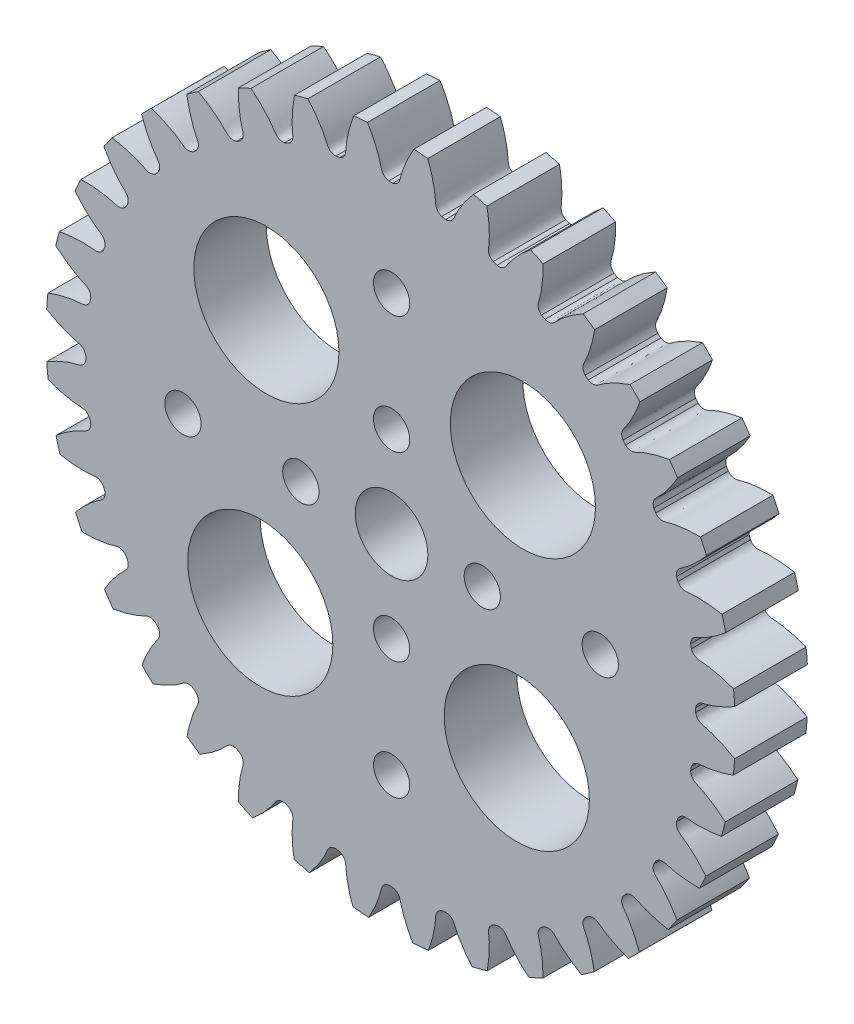
SolidWorks part; units mm, degrees
ref_plane "前视基准面" through (0, 0, 0) normal (0, 0, 1) x (1, 0, 0)
ref_plane "上视基准面" through (0, 0, 0) normal (0, 1, 0) x (1, 0, 0)
ref_plane "右视基准面" through (0, 0, 0) normal (1, 0, 0) x (0, 0, -1)
sketch "草图1" plane through (0, 0, 0) normal (0, 0, 1) x (1, 0, 0)
  circle A0 centre (-456.4903, -117.4676) radius 2
  circle A1 centre (-451.4903, -117.4676) radius 1
  circle A2 centre (-456.4903, -112.4676) radius 1
  circle A3 centre (-461.4903, -117.4676) radius 1
  circle A4 centre (-456.4903, -122.4676) radius 1
  arc A5 (-459.348, -100.9266) -> (-459.5644, -100.9647) centre (-456.5477, -117.4408) ccw
  arc A6 (-456.4282, -100.6904) -> (-456.648, -100.6904) centre (-456.5381, -117.44) ccw
  arc A7 (-454.4982, -98.5498) -> (-455.2571, -98.4832) centre (-456.5381, -117.44) ccw
  arc A8 (-453.5118, -100.9647) -> (-453.7282, -100.9266) centre (-456.5285, -117.4408) ccw
  arc A9 (-450.6873, -101.7414) -> (-450.8938, -101.6662) centre (-456.5192, -117.4433) ccw
  arc A10 (-448.0406, -102.9967) -> (-448.2309, -102.8868) centre (-456.5105, -117.4474) ccw
  arc A11 (-445.652, -104.6926) -> (-445.8204, -104.5513) centre (-456.5027, -117.4529) ccw
  arc A12 (-443.5943, -106.7774) -> (-443.7355, -106.6091) centre (-456.4959, -117.4597) ccw
  arc A13 (-441.9298, -109.1879) -> (-442.0397, -108.9976) centre (-456.4903, -117.4676) ccw
  arc A14 (-440.7092, -111.8508) -> (-440.7843, -111.6443) centre (-456.4863, -117.4763) ccw
  arc A15 (-439.9695, -114.6852) -> (-440.0077, -114.4688) centre (-456.4838, -117.4856) ccw
  arc A16 (-439.7333, -117.605) -> (-439.7333, -117.3853) centre (-456.483, -117.4951) ccw
  arc A17 (-440.0077, -120.5215) -> (-439.9695, -120.3051) centre (-456.4838, -117.5047) ccw
  arc A18 (-440.7843, -123.346) -> (-440.7092, -123.1395) centre (-456.4863, -117.514) ccw
  arc A19 (-442.0397, -125.9927) -> (-441.9298, -125.8024) centre (-456.4903, -117.5227) ccw
  arc A20 (-443.7355, -128.3812) -> (-443.5943, -128.2129) centre (-456.4959, -117.5306) ccw
  arc A21 (-445.8204, -130.439) -> (-445.652, -130.2977) centre (-456.5027, -117.5374) ccw
  arc A22 (-448.2309, -132.1035) -> (-448.0406, -131.9936) centre (-456.5105, -117.5429) ccw
  arc A23 (-450.8938, -133.3241) -> (-450.6873, -133.2489) centre (-456.5192, -117.547) ccw
  arc A24 (-453.7282, -134.0637) -> (-453.5118, -134.0256) centre (-456.5285, -117.5495) ccw
  arc A25 (-456.648, -134.2999) -> (-456.4282, -134.2999) centre (-456.5381, -117.5503) ccw
  arc A26 (-459.5644, -134.0256) -> (-459.348, -134.0637) centre (-456.5477, -117.5495) ccw
  arc A27 (-462.3889, -133.2489) -> (-462.1824, -133.3241) centre (-456.557, -117.547) ccw
  arc A28 (-465.0356, -131.9936) -> (-464.8454, -132.1035) centre (-456.5657, -117.5429) ccw
  arc A29 (-467.4242, -130.2977) -> (-467.2559, -130.439) centre (-456.5736, -117.5374) ccw
  arc A30 (-469.4819, -128.2129) -> (-469.3407, -128.3812) centre (-456.5804, -117.5306) ccw
  arc A31 (-471.1464, -125.8024) -> (-471.0365, -125.9927) centre (-456.5859, -117.5227) ccw
  arc A32 (-472.367, -123.1395) -> (-472.2919, -123.346) centre (-456.5899, -117.514) ccw
  arc A33 (-473.1067, -120.3051) -> (-473.0685, -120.5215) centre (-456.5924, -117.5047) ccw
  arc A34 (-473.3429, -117.3853) -> (-473.3429, -117.605) centre (-456.5933, -117.4951) ccw
  arc A35 (-473.0685, -114.4688) -> (-473.1067, -114.6852) centre (-456.5924, -117.4856) ccw
  arc A36 (-472.2919, -111.6443) -> (-472.367, -111.8508) centre (-456.5899, -117.4763) ccw
  arc A37 (-471.0365, -108.9976) -> (-471.1464, -109.1879) centre (-456.5859, -117.4676) ccw
  arc A38 (-469.3407, -106.6091) -> (-469.4819, -106.7774) centre (-456.5804, -117.4597) ccw
  arc A39 (-467.2559, -104.5513) -> (-467.4242, -104.6926) centre (-456.5736, -117.4529) ccw
  arc A40 (-464.8454, -102.8868) -> (-465.0357, -102.9967) centre (-456.5657, -117.4474) ccw
  arc A41 (-462.1824, -101.6662) -> (-462.3889, -101.7414) centre (-456.557, -117.4433) ccw
  arc A42 (-451.2389, -99.1939) -> (-451.9763, -98.9958) centre (-456.5381, -117.44) ccw
  arc A43 (-448.1414, -100.3961) -> (-448.8359, -100.0712) centre (-456.5381, -117.44) ccw
  arc A44 (-445.3006, -102.1194) -> (-445.9319, -101.6759) centre (-456.5381, -117.44) ccw
  arc A45 (-442.8037, -104.3111) -> (-443.3524, -103.7602) centre (-456.5381, -117.44) ccw
  arc A46 (-440.7271, -106.9037) -> (-441.1757, -106.2598) centre (-456.5381, -117.44) ccw
  arc A47 (-439.1341, -109.8175) -> (-439.4673, -109.098) centre (-456.5381, -117.44) ccw
  arc A48 (-438.0731, -112.963) -> (-438.2784, -112.1881) centre (-456.5381, -117.44) ccw
  arc A49 (-437.5758, -116.2437) -> (-437.6441, -115.4357) centre (-456.5381, -117.44) ccw
  arc A50 (-437.6567, -119.5593) -> (-437.5828, -118.7425) centre (-456.5381, -117.44) ccw
  arc A51 (-438.3123, -122.8086) -> (-438.0954, -122.0082) centre (-456.5381, -117.44) ccw
  arc A52 (-439.5219, -125.8928) -> (-439.1658, -125.1343) centre (-456.5381, -117.44) ccw
  arc A53 (-441.2477, -128.7185) -> (-440.7609, -128.0267) centre (-456.5381, -117.44) ccw
  arc A54 (-443.4365, -131.2004) -> (-442.8322, -130.5986) centre (-456.5381, -117.44) ccw
  arc A55 (-446.0213, -133.2639) -> (-445.317, -132.7725) centre (-456.5381, -117.44) ccw
  arc A56 (-448.9232, -134.8473) -> (-448.1403, -134.4834) centre (-456.5381, -117.44) ccw
  arc A57 (-452.0543, -135.9034) -> (-451.2172, -135.6797) centre (-456.5381, -117.44) ccw
  arc A58 (-455.3198, -136.4009) -> (-454.455, -136.3255) centre (-456.5381, -117.44) ccw
  arc A59 (-458.6212, -136.3255) -> (-457.7564, -136.4009) centre (-456.5381, -117.44) ccw
  arc A60 (-461.859, -135.6797) -> (-461.0219, -135.9034) centre (-456.5381, -117.44) ccw
  arc A61 (-464.9359, -134.4834) -> (-464.153, -134.8473) centre (-456.5381, -117.44) ccw
  arc A62 (-467.7592, -132.7725) -> (-467.0549, -133.2639) centre (-456.5381, -117.44) ccw
  arc A63 (-470.244, -130.5986) -> (-469.6397, -131.2004) centre (-456.5381, -117.44) ccw
  arc A64 (-472.3153, -128.0267) -> (-471.8285, -128.7185) centre (-456.5381, -117.44) ccw
  arc A65 (-473.9104, -125.1343) -> (-473.5543, -125.8928) centre (-456.5381, -117.44) ccw
  arc A66 (-474.9808, -122.0082) -> (-474.7639, -122.8086) centre (-456.5381, -117.44) ccw
  arc A67 (-475.4934, -118.7425) -> (-475.4195, -119.5593) centre (-456.5381, -117.44) ccw
  arc A68 (-475.4321, -115.4357) -> (-475.5004, -116.2437) centre (-456.5381, -117.44) ccw
  arc A69 (-474.7978, -112.1881) -> (-475.0031, -112.963) centre (-456.5381, -117.44) ccw
  arc A70 (-473.6089, -109.098) -> (-473.9421, -109.8175) centre (-456.5381, -117.44) ccw
  arc A71 (-471.9005, -106.2598) -> (-472.3491, -106.9037) centre (-456.5381, -117.44) ccw
  arc A72 (-469.7238, -103.7602) -> (-470.2725, -104.3111) centre (-456.5381, -117.44) ccw
  arc A73 (-467.1444, -101.6759) -> (-467.7756, -102.1194) centre (-456.5381, -117.44) ccw
  arc A74 (-464.2403, -100.0712) -> (-464.9348, -100.3961) centre (-456.5381, -117.44) ccw
  arc A75 (-461.0999, -98.9958) -> (-461.8373, -99.1939) centre (-456.5381, -117.44) ccw
  arc A76 (-457.8191, -98.4832) -> (-458.578, -98.5498) centre (-456.5381, -117.44) ccw
  circle A77 centre (-463.3906, -110.2298) radius 4
  circle A78 centre (-463.7281, -124.3679) radius 4
  circle A79 centre (-449.59, -124.7054) radius 4
  circle A80 centre (-449.2525, -110.5673) radius 4
  circle A81 centre (-456.4903, -128.9676) radius 1
  circle A82 centre (-444.9903, -117.4676) radius 1
  circle A83 centre (-456.4903, -105.9676) radius 1
  circle A84 centre (-467.9903, -117.4676) radius 1
  spline S0 degree 3 poles (-459.348, -100.9266) (-459.0074, -100.7845) (-459.0234, -100.515) (-458.9985, -100.2221) (-458.9898, -100.1383) (-458.9743, -100.0135) (-458.9476, -99.8415) (-458.9033, -99.6165) (-458.8439, -99.3672) (-458.7672, -99.0943) (-458.6778, -98.8188) (-458.6108, -98.6354) (-458.578, -98.5498) knots 0 0 0 0 0.120371 0.133303 0.147364 0.162556 0.19633 0.234626 0.277443 0.324782 0.376641 0.422597 0.422597 0.422597 0.422597
  spline S1 degree 3 poles (-456.648, -100.6904) (-457.0081, -100.6096) (-457.0391, -100.3414) (-457.1145, -100.0572) (-457.1376, -99.9763) (-457.1745, -99.8561) (-457.2308, -99.6913) (-457.3134, -99.4774) (-457.4153, -99.2422) (-457.5381, -98.9868) (-457.6741, -98.7309) (-457.7719, -98.5619) (-457.8191, -98.4832) knots 0 0 0 0 0.120371 0.133303 0.147364 0.162556 0.19633 0.234626 0.277443 0.324782 0.376641 0.422634 0.422634 0.422634 0.422634
  spline S2 degree 3 poles (-456.4282, -100.6904) (-456.0681, -100.6096) (-456.0371, -100.3414) (-455.9617, -100.0572) (-455.9386, -99.9763) (-455.9017, -99.8561) (-455.8454, -99.6913) (-455.7628, -99.4774) (-455.661, -99.2422) (-455.5381, -98.9868) (-455.4021, -98.7309) (-455.3043, -98.5619) (-455.2571, -98.4832) knots 0 0 0 0 0.120371 0.133303 0.147364 0.162556 0.19633 0.234626 0.277443 0.324782 0.376641 0.422634 0.422634 0.422634 0.422634
  spline S3 degree 3 poles (-453.7282, -100.9266) (-454.0688, -100.7845) (-454.0528, -100.515) (-454.0777, -100.2221) (-454.0864, -100.1383) (-454.1019, -100.0135) (-454.1286, -99.8415) (-454.1729, -99.6165) (-454.2323, -99.3672) (-454.309, -99.0943) (-454.3984, -98.8188) (-454.4654, -98.6354) (-454.4982, -98.5498) knots 0 0 0 0 0.120371 0.133303 0.147364 0.162556 0.19633 0.234626 0.277443 0.324782 0.376641 0.422597 0.422597 0.422597 0.422597
  spline S4 degree 3 poles (-453.5118, -100.9647) (-453.1431, -100.9477) (-453.066, -100.689) (-452.9424, -100.4223) (-452.9056, -100.3465) (-452.8484, -100.2346) (-452.7644, -100.082) (-452.6458, -99.8858) (-452.5047, -99.6718) (-452.3393, -99.4416) (-452.1613, -99.2137) (-452.0361, -99.0646) (-451.9763, -98.9958) knots 0 0 0 0 0.120371 0.133303 0.147364 0.162556 0.19633 0.234626 0.277443 0.324782 0.376641 0.422355 0.422355 0.422355 0.422355
  spline S5 degree 3 poles (-450.8938, -101.6662) (-451.2045, -101.4672) (-451.1419, -101.2045) (-451.1157, -100.9117) (-451.1096, -100.8278) (-451.1032, -100.7022) (-451.0997, -100.5281) (-451.1042, -100.2988) (-451.1195, -100.043) (-451.1476, -99.7609) (-451.1877, -99.4748) (-451.2217, -99.2833) (-451.2389, -99.1939) knots 0 0 0 0 0.120371 0.133303 0.147364 0.162556 0.19633 0.234626 0.277443 0.324782 0.376641 0.422247 0.422247 0.422247 0.422247
  spline S6 degree 3 poles (-450.6873, -101.7414) (-450.3213, -101.7887) (-450.2004, -101.5472) (-450.0323, -101.306) (-449.983, -101.2378) (-449.9071, -101.1375) (-449.7979, -101.0019) (-449.6471, -100.8292) (-449.471, -100.643) (-449.2682, -100.445) (-449.0542, -100.2522) (-448.9058, -100.1279) (-448.8359, -100.0712) knots 0 0 0 0 0.120371 0.133303 0.147364 0.162556 0.19633 0.234626 0.277443 0.324782 0.376641 0.421771 0.421771 0.421771 0.421771
  spline S7 degree 3 poles (-448.2309, -102.8868) (-448.5023, -102.6368) (-448.3951, -102.389) (-448.3184, -102.1053) (-448.2979, -102.0236) (-448.2697, -101.9011) (-448.236, -101.7302) (-448.2007, -101.5037) (-448.1712, -101.249) (-448.15, -100.9664) (-448.1399, -100.6789) (-448.14, -100.4857) (-448.1414, -100.3961) knots 0 0 0 0 0.120371 0.133303 0.147364 0.162556 0.19633 0.234626 0.277443 0.324782 0.376641 0.421594 0.421594 0.421594 0.421594
  spline S8 degree 3 poles (-448.0406, -102.9967) (-447.6883, -103.1068) (-447.5273, -102.89) (-447.3199, -102.6817) (-447.2595, -102.6231) (-447.1674, -102.5375) (-447.0363, -102.4229) (-446.8578, -102.279) (-446.652, -102.1262) (-446.4179, -101.9665) (-446.1751, -101.8147) (-446.009, -101.7188) (-445.9319, -101.6759) knots 0 0 0 0 0.120371 0.133303 0.147364 0.162556 0.19633 0.234626 0.277443 0.324782 0.376641 0.420899 0.420899 0.420899 0.420899
  spline S9 degree 3 poles (-445.8204, -104.5513) (-446.0443, -104.258) (-445.8957, -104.0326) (-445.7708, -103.7664) (-445.7364, -103.6896) (-445.6875, -103.5737) (-445.6246, -103.4113) (-445.5504, -103.1944) (-445.4773, -102.9487) (-445.4072, -102.6741) (-445.3477, -102.3946) (-445.3145, -102.2062) (-445.3006, -102.1194) knots 0 0 0 0 0.120371 0.133303 0.147364 0.162556 0.19633 0.234626 0.277443 0.324782 0.376641 0.420658 0.420658 0.420658 0.420658
  spline S10 degree 3 poles (-445.652, -104.6926) (-445.3243, -104.8621) (-445.1281, -104.6766) (-444.8877, -104.5075) (-444.818, -104.4603) (-444.7124, -104.3919) (-444.5634, -104.3018) (-444.3626, -104.1911) (-444.1334, -104.0764) (-443.8751, -103.9597) (-443.6118, -103.8533) (-443.4337, -103.7884) (-443.3524, -103.7602) knots 0 0 0 0 0.120371 0.133303 0.147364 0.162556 0.19633 0.234626 0.277443 0.324782 0.376641 0.419767 0.419767 0.419767 0.419767
  spline S11 degree 3 poles (-443.7355, -106.6091) (-443.9051, -106.2813) (-443.7196, -106.0851) (-443.5504, -105.8447) (-443.5032, -105.775) (-443.4349, -105.6694) (-443.3448, -105.5204) (-443.2341, -105.3197) (-443.1193, -105.0904) (-443.0027, -104.8321) (-442.8964, -104.5694) (-442.8318, -104.3918) (-442.8037, -104.3111) knots 0 0 0 0 0.120371 0.133303 0.147364 0.162556 0.19633 0.234626 0.277443 0.324782 0.376641 0.419468 0.419468 0.419468 0.419468
  spline S12 degree 3 poles (-443.5943, -106.7774) (-443.3009, -107.0013) (-443.0755, -106.8527) (-442.8094, -106.7279) (-442.7325, -106.6935) (-442.6167, -106.6445) (-442.4543, -106.5816) (-442.2374, -106.5075) (-441.9917, -106.4343) (-441.7171, -106.3643) (-441.4419, -106.3057) (-441.258, -106.2732) (-441.1757, -106.2598) knots 0 0 0 0 0.120371 0.133303 0.147364 0.162556 0.19633 0.234626 0.277443 0.324782 0.376641 0.418409 0.418409 0.418409 0.418409
  spline S13 degree 3 poles (-442.0397, -108.9976) (-442.1498, -108.6454) (-441.933, -108.4844) (-441.7247, -108.277) (-441.6661, -108.2165) (-441.5804, -108.1245) (-441.4658, -107.9933) (-441.3219, -107.8148) (-441.1691, -107.609) (-441.0094, -107.3749) (-440.8606, -107.137) (-440.7675, -106.9759) (-440.7271, -106.9037) knots 0 0 0 0 0.120371 0.133303 0.147364 0.162556 0.19633 0.234626 0.277443 0.324782 0.376641 0.418059 0.418059 0.418059 0.418059
  spline S14 degree 3 poles (-441.9298, -109.1879) (-441.6798, -109.4594) (-441.432, -109.3521) (-441.1482, -109.2754) (-441.0666, -109.2549) (-440.944, -109.2268) (-440.7732, -109.1931) (-440.5466, -109.1577) (-440.292, -109.1283) (-440.0094, -109.107) (-439.7313, -109.0972) (-439.5476, -109.097) (-439.4673, -109.098) knots 0 0 0 0 0.120371 0.133303 0.147364 0.162556 0.19633 0.234626 0.277443 0.324782 0.376641 0.416867 0.416867 0.416867 0.416867
  spline S15 degree 3 poles (-440.7843, -111.6443) (-440.8316, -111.2783) (-440.5902, -111.1574) (-440.349, -110.9894) (-440.2808, -110.94) (-440.1805, -110.8642) (-440.0448, -110.755) (-439.8721, -110.6042) (-439.6859, -110.428) (-439.488, -110.2252) (-439.3023, -110.0191) (-439.1845, -109.879) (-439.1341, -109.8175) knots 0 0 0 0 0.120371 0.133303 0.147364 0.162556 0.19633 0.234626 0.277443 0.324782 0.376641 0.416476 0.416476 0.416476 0.416476
  spline S16 degree 3 poles (-440.7092, -111.8508) (-440.5101, -112.1616) (-440.2475, -112.099) (-439.9547, -112.0727) (-439.8707, -112.0667) (-439.7451, -112.0603) (-439.571, -112.0567) (-439.3418, -112.0613) (-439.0859, -112.0765) (-438.8039, -112.1046) (-438.5317, -112.1428) (-438.354, -112.1738) (-438.2784, -112.1881) knots 0 0 0 0 0.120371 0.133303 0.147364 0.162556 0.19633 0.234626 0.277443 0.324782 0.376641 0.415189 0.415189 0.415189 0.415189
  spline S17 degree 3 poles (-440.0077, -114.4688) (-439.9907, -114.1002) (-439.7319, -114.023) (-439.4652, -113.8994) (-439.3895, -113.8626) (-439.2775, -113.8054) (-439.125, -113.7214) (-438.9287, -113.6029) (-438.7147, -113.4617) (-438.4846, -113.2964) (-438.2686, -113.1277) (-438.1308, -113.0126) (-438.0731, -112.963) knots 0 0 0 0 0.120371 0.133303 0.147364 0.162556 0.19633 0.234626 0.277443 0.324782 0.376641 0.414768 0.414768 0.414768 0.414768
  spline S18 degree 3 poles (-439.9695, -114.6852) (-439.8275, -115.0258) (-439.5579, -115.0098) (-439.265, -115.0348) (-439.1813, -115.0434) (-439.0565, -115.0589) (-438.8844, -115.0857) (-438.6595, -115.1299) (-438.4101, -115.1894) (-438.1373, -115.266) (-437.8792, -115.3498) (-437.7128, -115.4099) (-437.6441, -115.4357) knots 0 0 0 0 0.120371 0.133303 0.147364 0.162556 0.19633 0.234626 0.277443 0.324782 0.376641 0.413425 0.413425 0.413425 0.413425
  spline S19 degree 3 poles (-439.7333, -117.3853) (-439.6526, -117.0252) (-439.3843, -116.9942) (-439.1002, -116.9187) (-439.0193, -116.8956) (-438.899, -116.8587) (-438.7342, -116.8025) (-438.5204, -116.7198) (-438.2851, -116.618) (-438.0298, -116.4951) (-437.7909, -116.3682) (-437.6382, -116.2806) (-437.5758, -116.2437) knots 0 0 0 0 0.120371 0.133303 0.147364 0.162556 0.19633 0.234626 0.277443 0.324782 0.376641 0.412986 0.412986 0.412986 0.412986
  spline S20 degree 3 poles (-439.7333, -117.605) (-439.6526, -117.9651) (-439.3843, -117.9961) (-439.1002, -118.0716) (-439.0193, -118.0946) (-438.899, -118.1316) (-438.7342, -118.1878) (-438.5204, -118.2704) (-438.2851, -118.3723) (-438.0298, -118.4952) (-437.7933, -118.6208) (-437.6429, -118.707) (-437.5828, -118.7425) knots 0 0 0 0 0.120371 0.133303 0.147364 0.162556 0.19633 0.234626 0.277443 0.324782 0.376641 0.411628 0.411628 0.411628 0.411628
  spline S21 degree 3 poles (-439.9695, -120.3051) (-439.8275, -119.9645) (-439.5579, -119.9805) (-439.265, -119.9555) (-439.1813, -119.9469) (-439.0565, -119.9314) (-438.8844, -119.9046) (-438.6595, -119.8604) (-438.4101, -119.8009) (-438.1373, -119.7242) (-437.8834, -119.6418) (-437.7212, -119.5834) (-437.6567, -119.5593) knots 0 0 0 0 0.120371 0.133303 0.147364 0.162556 0.19633 0.234626 0.277443 0.324782 0.376641 0.411185 0.411185 0.411185 0.411185
  spline S22 degree 3 poles (-440.0077, -120.5215) (-439.9907, -120.8901) (-439.7319, -120.9673) (-439.4652, -121.0909) (-439.3895, -121.1277) (-439.2775, -121.1849) (-439.125, -121.2689) (-438.9287, -121.3874) (-438.7147, -121.5286) (-438.4846, -121.6939) (-438.2763, -121.8566) (-438.1459, -121.9652) (-438.0954, -122.0082) knots 0 0 0 0 0.120371 0.133303 0.147364 0.162556 0.19633 0.234626 0.277443 0.324782 0.376641 0.409854 0.409854 0.409854 0.409854
  spline S23 degree 3 poles (-440.7092, -123.1395) (-440.5101, -122.8287) (-440.2475, -122.8913) (-439.9547, -122.9176) (-439.8707, -122.9236) (-439.7451, -122.93) (-439.571, -122.9335) (-439.3418, -122.929) (-439.0859, -122.9138) (-438.8039, -122.8857) (-438.5431, -122.8491) (-438.3767, -122.8204) (-438.3123, -122.8086) knots 0 0 0 0 0.120371 0.133303 0.147364 0.162556 0.19633 0.234626 0.277443 0.324782 0.376641 0.40942 0.40942 0.40942 0.40942
  spline S24 degree 3 poles (-440.7843, -123.346) (-440.8316, -123.712) (-440.5902, -123.8329) (-440.349, -124.0009) (-440.2808, -124.0503) (-440.1805, -124.1261) (-440.0448, -124.2353) (-439.8721, -124.3861) (-439.6859, -124.5623) (-439.488, -124.7651) (-439.3134, -124.9589) (-439.2059, -125.0859) (-439.1658, -125.1343) knots 0 0 0 0 0.120371 0.133303 0.147364 0.162556 0.19633 0.234626 0.277443 0.324782 0.376641 0.408156 0.408156 0.408156 0.408156
  spline S25 degree 3 poles (-441.9298, -125.8024) (-441.6798, -125.5309) (-441.432, -125.6382) (-441.1482, -125.7149) (-441.0666, -125.7354) (-440.944, -125.7635) (-440.7732, -125.7972) (-440.5466, -125.8326) (-440.292, -125.862) (-440.0094, -125.8833) (-439.7495, -125.8924) (-439.584, -125.8932) (-439.5219, -125.8928) knots 0 0 0 0 0.120371 0.133303 0.147364 0.162556 0.19633 0.234626 0.277443 0.324782 0.376641 0.407744 0.407744 0.407744 0.407744
  spline S26 degree 3 poles (-442.0397, -125.9927) (-442.1498, -126.3449) (-441.933, -126.5059) (-441.7247, -126.7133) (-441.6661, -126.7738) (-441.5804, -126.8658) (-441.4658, -126.9969) (-441.3219, -127.1754) (-441.1691, -127.3813) (-441.0094, -127.6154) (-440.8728, -127.8339) (-440.7905, -127.9748) (-440.7609, -128.0267) knots 0 0 0 0 0.120371 0.133303 0.147364 0.162556 0.19633 0.234626 0.277443 0.324782 0.376641 0.406585 0.406585 0.406585 0.406585
  spline S27 degree 3 poles (-443.5943, -128.2129) (-443.3009, -127.989) (-443.0755, -128.1376) (-442.8094, -128.2624) (-442.7325, -128.2968) (-442.6167, -128.3458) (-442.4543, -128.4086) (-442.2374, -128.4828) (-441.9917, -128.556) (-441.7171, -128.626) (-441.4657, -128.6795) (-441.3059, -128.7085) (-441.2477, -128.7185) knots 0 0 0 0 0.120371 0.133303 0.147364 0.162556 0.19633 0.234626 0.277443 0.324782 0.376641 0.406209 0.406209 0.406209 0.406209
  spline S28 degree 3 poles (-443.7355, -128.3812) (-443.9051, -128.709) (-443.7196, -128.9052) (-443.5504, -129.1456) (-443.5032, -129.2153) (-443.4349, -129.3208) (-443.3448, -129.4699) (-443.2341, -129.6706) (-443.1193, -129.8999) (-443.0027, -130.1582) (-442.9071, -130.3945) (-442.8514, -130.545) (-442.8322, -130.5986) knots 0 0 0 0 0.120371 0.133303 0.147364 0.162556 0.19633 0.234626 0.277443 0.324782 0.376641 0.405188 0.405188 0.405188 0.405188
  spline S29 degree 3 poles (-445.652, -130.2977) (-445.3243, -130.1281) (-445.1281, -130.3137) (-444.8877, -130.4828) (-444.818, -130.53) (-444.7124, -130.5984) (-444.5634, -130.6885) (-444.3626, -130.7992) (-444.1334, -130.9139) (-443.8751, -131.0306) (-443.6394, -131.1259) (-443.4895, -131.1814) (-443.4365, -131.2004) knots 0 0 0 0 0.120371 0.133303 0.147364 0.162556 0.19633 0.234626 0.277443 0.324782 0.376641 0.404861 0.404861 0.404861 0.404861
  spline S30 degree 3 poles (-445.8204, -130.439) (-446.0443, -130.7323) (-445.8957, -130.9577) (-445.7708, -131.2239) (-445.7364, -131.3007) (-445.6875, -131.4165) (-445.6246, -131.5789) (-445.5504, -131.7959) (-445.4773, -132.0416) (-445.4072, -132.3162) (-445.3547, -132.5632) (-445.3263, -132.7187) (-445.317, -132.7725) knots 0 0 0 0 0.120371 0.133303 0.147364 0.162556 0.19633 0.234626 0.277443 0.324782 0.376641 0.404007 0.404007 0.404007 0.404007
  spline S31 degree 3 poles (-448.0406, -131.9936) (-447.6883, -131.8835) (-447.5273, -132.1003) (-447.3199, -132.3086) (-447.2595, -132.3672) (-447.1674, -132.4528) (-447.0363, -132.5674) (-446.8578, -132.7113) (-446.652, -132.8641) (-446.4179, -133.0238) (-446.2042, -133.1575) (-446.0682, -133.2371) (-446.0213, -133.2639) knots 0 0 0 0 0.120371 0.133303 0.147364 0.162556 0.19633 0.234626 0.277443 0.324782 0.376641 0.40374 0.40374 0.40374 0.40374
  spline S32 degree 3 poles (-448.2309, -132.1035) (-448.5023, -132.3534) (-448.3951, -132.6013) (-448.3184, -132.885) (-448.2979, -132.9667) (-448.2697, -133.0892) (-448.236, -133.2601) (-448.2007, -133.4866) (-448.1712, -133.7413) (-448.15, -134.0239) (-448.1412, -134.2744) (-448.1402, -134.4307) (-448.1403, -134.4834) knots 0 0 0 0 0.120371 0.133303 0.147364 0.162556 0.19633 0.234626 0.277443 0.324782 0.376641 0.403078 0.403078 0.403078 0.403078
  spline S33 degree 3 poles (-450.6873, -133.2489) (-450.3213, -133.2016) (-450.2004, -133.4431) (-450.0323, -133.6843) (-449.983, -133.7524) (-449.9071, -133.8528) (-449.7979, -133.9884) (-449.6471, -134.1611) (-449.471, -134.3473) (-449.2682, -134.5453) (-449.0822, -134.7128) (-448.9634, -134.8138) (-448.9232, -134.8473) knots 0 0 0 0 0.120371 0.133303 0.147364 0.162556 0.19633 0.234626 0.277443 0.324782 0.376641 0.40288 0.40288 0.40288 0.40288
  spline S34 degree 3 poles (-450.8938, -133.3241) (-451.2045, -133.5231) (-451.1419, -133.7858) (-451.1157, -134.0786) (-451.1096, -134.1625) (-451.1032, -134.2881) (-451.0997, -134.4622) (-451.1042, -134.6914) (-451.1195, -134.9473) (-451.1476, -135.2293) (-451.1822, -135.4763) (-451.2081, -135.6291) (-451.2172, -135.6797) knots 0 0 0 0 0.120371 0.133303 0.147364 0.162556 0.19633 0.234626 0.277443 0.324782 0.376641 0.402428 0.402428 0.402428 0.402428
  spline S35 degree 3 poles (-453.5118, -134.0256) (-453.1431, -134.0426) (-453.066, -134.3013) (-452.9424, -134.568) (-452.9056, -134.6437) (-452.8484, -134.7557) (-452.7644, -134.9083) (-452.6458, -135.1045) (-452.5047, -135.3185) (-452.3393, -135.5487) (-452.186, -135.7451) (-452.0873, -135.8642) (-452.0543, -135.9034) knots 0 0 0 0 0.120371 0.133303 0.147364 0.162556 0.19633 0.234626 0.277443 0.324782 0.376641 0.402306 0.402306 0.402306 0.402306
  spline S36 degree 3 poles (-453.7282, -134.0637) (-454.0688, -134.2058) (-454.0528, -134.4753) (-454.0777, -134.7682) (-454.0864, -134.852) (-454.1019, -134.9768) (-454.1286, -135.1488) (-454.1729, -135.3738) (-454.2323, -135.6231) (-454.309, -135.896) (-454.3858, -136.1325) (-454.4376, -136.2778) (-454.455, -136.3255) knots 0 0 0 0 0.120371 0.133303 0.147364 0.162556 0.19633 0.234626 0.277443 0.324782 0.376641 0.402077 0.402077 0.402077 0.402077
  spline S37 degree 3 poles (-456.4282, -134.2999) (-456.0681, -134.3807) (-456.0371, -134.6489) (-455.9617, -134.933) (-455.9386, -135.014) (-455.9017, -135.1342) (-455.8454, -135.299) (-455.7628, -135.5129) (-455.661, -135.7481) (-455.5381, -136.0035) (-455.4214, -136.2231) (-455.3452, -136.3571) (-455.3198, -136.4009) knots 0 0 0 0 0.120371 0.133303 0.147364 0.162556 0.19633 0.234626 0.277443 0.324782 0.376641 0.402036 0.402036 0.402036 0.402036
  spline S38 degree 3 poles (-456.648, -134.2999) (-457.0081, -134.3807) (-457.0391, -134.6489) (-457.1145, -134.933) (-457.1376, -135.014) (-457.1745, -135.1342) (-457.2308, -135.299) (-457.3134, -135.5129) (-457.4152, -135.7481) (-457.5381, -136.0035) (-457.6548, -136.2231) (-457.731, -136.3571) (-457.7564, -136.4009) knots 0 0 0 0 0.120371 0.133303 0.147364 0.162556 0.19633 0.234626 0.277443 0.324782 0.376641 0.402036 0.402036 0.402036 0.402036
  spline S39 degree 3 poles (-459.348, -134.0637) (-459.0074, -134.2058) (-459.0234, -134.4753) (-458.9985, -134.7682) (-458.9898, -134.852) (-458.9743, -134.9768) (-458.9476, -135.1488) (-458.9033, -135.3738) (-458.8439, -135.6231) (-458.7672, -135.896) (-458.6904, -136.1325) (-458.6386, -136.2778) (-458.6212, -136.3255) knots 0 0 0 0 0.120371 0.133303 0.147364 0.162556 0.19633 0.234626 0.277443 0.324782 0.376641 0.402077 0.402077 0.402077 0.402077
  spline S40 degree 3 poles (-459.5644, -134.0256) (-459.9331, -134.0426) (-460.0102, -134.3013) (-460.1338, -134.568) (-460.1706, -134.6437) (-460.2279, -134.7557) (-460.3119, -134.9083) (-460.4304, -135.1045) (-460.5715, -135.3185) (-460.7369, -135.5487) (-460.8902, -135.7451) (-460.9889, -135.8642) (-461.0219, -135.9034) knots 0 0 0 0 0.120371 0.133303 0.147364 0.162556 0.19633 0.234626 0.277443 0.324782 0.376641 0.402307 0.402307 0.402307 0.402307
  spline S41 degree 3 poles (-462.1824, -133.3241) (-461.8717, -133.5231) (-461.9343, -133.7858) (-461.9605, -134.0786) (-461.9666, -134.1625) (-461.973, -134.2881) (-461.9765, -134.4622) (-461.972, -134.6914) (-461.9567, -134.9473) (-461.9286, -135.2293) (-461.894, -135.4763) (-461.8681, -135.6291) (-461.859, -135.6797) knots 0 0 0 0 0.120371 0.133303 0.147364 0.162556 0.19633 0.234626 0.277443 0.324782 0.376641 0.402428 0.402428 0.402428 0.402428
  spline S42 degree 3 poles (-462.3889, -133.2489) (-462.7549, -133.2016) (-462.8758, -133.4431) (-463.0439, -133.6843) (-463.0932, -133.7524) (-463.1691, -133.8528) (-463.2783, -133.9884) (-463.4291, -134.1611) (-463.6052, -134.3473) (-463.8081, -134.5453) (-463.994, -134.7128) (-464.1128, -134.8138) (-464.153, -134.8473) knots 0 0 0 0 0.120371 0.133303 0.147364 0.162556 0.19633 0.234626 0.277443 0.324782 0.376641 0.40288 0.40288 0.40288 0.40288
  spline S43 degree 3 poles (-464.8454, -132.1035) (-464.5739, -132.3534) (-464.6811, -132.6013) (-464.7578, -132.885) (-464.7784, -132.9667) (-464.8065, -133.0892) (-464.8402, -133.2601) (-464.8755, -133.4866) (-464.905, -133.7413) (-464.9262, -134.0239) (-464.935, -134.2744) (-464.936, -134.4307) (-464.9359, -134.4834) knots 0 0 0 0 0.120371 0.133303 0.147364 0.162556 0.19633 0.234626 0.277443 0.324782 0.376641 0.403078 0.403078 0.403078 0.403078
  spline S44 degree 3 poles (-465.0356, -131.9936) (-465.3879, -131.8835) (-465.5489, -132.1003) (-465.7563, -132.3086) (-465.8167, -132.3672) (-465.9088, -132.4528) (-466.0399, -132.5674) (-466.2184, -132.7113) (-466.4242, -132.8641) (-466.6583, -133.0238) (-466.872, -133.1575) (-467.008, -133.2371) (-467.0549, -133.2639) knots 0 0 0 0 0.120371 0.133303 0.147364 0.162556 0.19633 0.234626 0.277443 0.324782 0.376641 0.40374 0.40374 0.40374 0.40374
  spline S45 degree 3 poles (-467.2559, -130.439) (-467.0319, -130.7323) (-467.1806, -130.9577) (-467.3054, -131.2239) (-467.3398, -131.3007) (-467.3887, -131.4165) (-467.4516, -131.5789) (-467.5258, -131.7959) (-467.599, -132.0416) (-467.669, -132.3162) (-467.7216, -132.5632) (-467.7499, -132.7187) (-467.7592, -132.7725) knots 0 0 0 0 0.120371 0.133303 0.147364 0.162556 0.19633 0.234626 0.277443 0.324782 0.376641 0.404007 0.404007 0.404007 0.404007
  spline S46 degree 3 poles (-467.4242, -130.2977) (-467.7519, -130.1281) (-467.9481, -130.3137) (-468.1885, -130.4828) (-468.2582, -130.53) (-468.3638, -130.5984) (-468.5128, -130.6885) (-468.7136, -130.7992) (-468.9428, -130.9139) (-469.2011, -131.0306) (-469.4369, -131.1259) (-469.5867, -131.1814) (-469.6397, -131.2004) knots 0 0 0 0 0.120371 0.133303 0.147364 0.162556 0.19633 0.234626 0.277443 0.324782 0.376641 0.404861 0.404861 0.404861 0.404861
  spline S47 degree 3 poles (-469.3407, -128.3812) (-469.1711, -128.709) (-469.3566, -128.9052) (-469.5258, -129.1456) (-469.573, -129.2153) (-469.6413, -129.3209) (-469.7314, -129.4699) (-469.8421, -129.6706) (-469.9569, -129.8999) (-470.0735, -130.1582) (-470.1691, -130.3945) (-470.2248, -130.545) (-470.244, -130.5986) knots 0 0 0 0 0.120371 0.133303 0.147364 0.162556 0.19633 0.234626 0.277443 0.324782 0.376641 0.405188 0.405188 0.405188 0.405188
  spline S48 degree 3 poles (-469.4819, -128.2129) (-469.7753, -127.989) (-470.0007, -128.1376) (-470.2668, -128.2624) (-470.3437, -128.2968) (-470.4595, -128.3458) (-470.6219, -128.4086) (-470.8388, -128.4828) (-471.0845, -128.556) (-471.3591, -128.626) (-471.6105, -128.6795) (-471.7703, -128.7085) (-471.8285, -128.7185) knots 0 0 0 0 0.120371 0.133303 0.147364 0.162556 0.19633 0.234626 0.277443 0.324782 0.376641 0.406209 0.406209 0.406209 0.406209
  spline S49 degree 3 poles (-471.0365, -125.9927) (-470.9264, -126.3449) (-471.1432, -126.5059) (-471.3515, -126.7133) (-471.4101, -126.7738) (-471.4958, -126.8658) (-471.6104, -126.9969) (-471.7543, -127.1754) (-471.9071, -127.3813) (-472.0668, -127.6154) (-472.2034, -127.8339) (-472.2857, -127.9748) (-472.3153, -128.0267) knots 0 0 0 0 0.120371 0.133303 0.147364 0.162556 0.19633 0.234626 0.277443 0.324782 0.376641 0.406585 0.406585 0.406585 0.406585
  spline S50 degree 3 poles (-471.1464, -125.8024) (-471.3964, -125.5309) (-471.6442, -125.6382) (-471.928, -125.7149) (-472.0096, -125.7354) (-472.1322, -125.7635) (-472.303, -125.7972) (-472.5296, -125.8326) (-472.7842, -125.862) (-473.0668, -125.8833) (-473.3267, -125.8924) (-473.4922, -125.8932) (-473.5543, -125.8928) knots 0 0 0 0 0.120371 0.133303 0.147364 0.162556 0.19633 0.234626 0.277443 0.324782 0.376641 0.407744 0.407744 0.407744 0.407744
  spline S51 degree 3 poles (-472.2919, -123.346) (-472.2446, -123.712) (-472.486, -123.8329) (-472.7272, -124.0009) (-472.7954, -124.0503) (-472.8957, -124.1261) (-473.0314, -124.2353) (-473.2041, -124.3861) (-473.3903, -124.5623) (-473.5882, -124.7651) (-473.7628, -124.9589) (-473.8703, -125.0859) (-473.9104, -125.1343) knots 0 0 0 0 0.120371 0.133303 0.147364 0.162556 0.19633 0.234626 0.277443 0.324782 0.376641 0.408156 0.408156 0.408156 0.408156
  spline S52 degree 3 poles (-472.367, -123.1395) (-472.5661, -122.8287) (-472.8287, -122.8913) (-473.1215, -122.9176) (-473.2055, -122.9236) (-473.3311, -122.93) (-473.5052, -122.9335) (-473.7344, -122.929) (-473.9903, -122.9138) (-474.2723, -122.8857) (-474.5331, -122.8491) (-474.6996, -122.8204) (-474.7639, -122.8086) knots 0 0 0 0 0.120371 0.133303 0.147364 0.162556 0.19633 0.234626 0.277443 0.324782 0.376641 0.40942 0.40942 0.40942 0.40942
  spline S53 degree 3 poles (-473.0685, -120.5215) (-473.0855, -120.8901) (-473.3443, -120.9673) (-473.611, -121.0909) (-473.6867, -121.1277) (-473.7987, -121.1849) (-473.9512, -121.2689) (-474.1475, -121.3874) (-474.3615, -121.5286) (-474.5916, -121.6939) (-474.7999, -121.8566) (-474.9303, -121.9652) (-474.9808, -122.0082) knots 0 0 0 0 0.120371 0.133303 0.147364 0.162556 0.19633 0.234626 0.277443 0.324782 0.376641 0.409855 0.409855 0.409855 0.409855
  spline S54 degree 3 poles (-473.1067, -120.3051) (-473.2487, -119.9645) (-473.5183, -119.9805) (-473.8112, -119.9555) (-473.8949, -119.9469) (-474.0197, -119.9314) (-474.1918, -119.9046) (-474.4167, -119.8604) (-474.6661, -119.8009) (-474.9389, -119.7242) (-475.1928, -119.6418) (-475.355, -119.5834) (-475.4195, -119.5593) knots 0 0 0 0 0.120371 0.133303 0.147364 0.162556 0.19633 0.234626 0.277443 0.324782 0.376641 0.411185 0.411185 0.411185 0.411185
  spline S55 degree 3 poles (-473.3429, -117.605) (-473.4237, -117.9651) (-473.6919, -117.9961) (-473.976, -118.0716) (-474.057, -118.0946) (-474.1772, -118.1316) (-474.342, -118.1878) (-474.5558, -118.2704) (-474.7911, -118.3723) (-475.0465, -118.4952) (-475.2829, -118.6208) (-475.4333, -118.707) (-475.4934, -118.7425) knots 0 0 0 0 0.120371 0.133303 0.147364 0.162556 0.19633 0.234626 0.277443 0.324782 0.376641 0.411629 0.411629 0.411629 0.411629
  spline S56 degree 3 poles (-473.3429, -117.3853) (-473.4237, -117.0252) (-473.6919, -116.9942) (-473.976, -116.9187) (-474.057, -116.8956) (-474.1772, -116.8587) (-474.342, -116.8025) (-474.5558, -116.7198) (-474.7911, -116.618) (-475.0465, -116.4951) (-475.2853, -116.3682) (-475.438, -116.2806) (-475.5004, -116.2437) knots 0 0 0 0 0.120371 0.133303 0.147364 0.162556 0.19633 0.234626 0.277443 0.324782 0.376641 0.412986 0.412986 0.412986 0.412986
  spline S57 degree 3 poles (-473.1067, -114.6852) (-473.2487, -115.0258) (-473.5183, -115.0098) (-473.8112, -115.0348) (-473.8949, -115.0434) (-474.0197, -115.0589) (-474.1918, -115.0857) (-474.4167, -115.1299) (-474.6661, -115.1894) (-474.9389, -115.266) (-475.197, -115.3498) (-475.3634, -115.4099) (-475.4321, -115.4357) knots 0 0 0 0 0.120371 0.133303 0.147364 0.162556 0.19633 0.234626 0.277443 0.324782 0.376641 0.413425 0.413425 0.413425 0.413425
  spline S58 degree 3 poles (-473.0685, -114.4688) (-473.0855, -114.1002) (-473.3443, -114.023) (-473.611, -113.8994) (-473.6867, -113.8626) (-473.7987, -113.8054) (-473.9512, -113.7214) (-474.1475, -113.6029) (-474.3615, -113.4617) (-474.5916, -113.2964) (-474.8076, -113.1277) (-474.9454, -113.0126) (-475.0031, -112.963) knots 0 0 0 0 0.120371 0.133303 0.147364 0.162556 0.19633 0.234626 0.277443 0.324782 0.376641 0.414768 0.414768 0.414768 0.414768
  spline S59 degree 3 poles (-472.367, -111.8508) (-472.5661, -112.1616) (-472.8287, -112.099) (-473.1215, -112.0727) (-473.2055, -112.0667) (-473.3311, -112.0603) (-473.5052, -112.0568) (-473.7344, -112.0613) (-473.9903, -112.0765) (-474.2723, -112.1046) (-474.5445, -112.1428) (-474.7222, -112.1738) (-474.7978, -112.1881) knots 0 0 0 0 0.120371 0.133303 0.147364 0.162556 0.19633 0.234626 0.277443 0.324782 0.376641 0.415189 0.415189 0.415189 0.415189
  spline S60 degree 3 poles (-472.2919, -111.6443) (-472.2446, -111.2783) (-472.486, -111.1574) (-472.7272, -110.9894) (-472.7954, -110.94) (-472.8957, -110.8642) (-473.0314, -110.755) (-473.2041, -110.6042) (-473.3903, -110.428) (-473.5882, -110.2252) (-473.774, -110.0191) (-473.8917, -109.879) (-473.9421, -109.8175) knots 0 0 0 0 0.120371 0.133303 0.147364 0.162556 0.19633 0.234626 0.277443 0.324782 0.376641 0.416477 0.416477 0.416477 0.416477
  spline S61 degree 3 poles (-471.1464, -109.1879) (-471.3964, -109.4594) (-471.6442, -109.3521) (-471.928, -109.2754) (-472.0096, -109.2549) (-472.1322, -109.2268) (-472.303, -109.1931) (-472.5296, -109.1577) (-472.7842, -109.1283) (-473.0668, -109.107) (-473.3449, -109.0972) (-473.5286, -109.097) (-473.6089, -109.098) knots 0 0 0 0 0.120371 0.133303 0.147364 0.162556 0.19633 0.234626 0.277443 0.324782 0.376641 0.416867 0.416867 0.416867 0.416867
  spline S62 degree 3 poles (-471.0365, -108.9976) (-470.9264, -108.6454) (-471.1432, -108.4844) (-471.3516, -108.277) (-471.4101, -108.2165) (-471.4958, -108.1245) (-471.6104, -107.9933) (-471.7543, -107.8149) (-471.9071, -107.609) (-472.0668, -107.3749) (-472.2156, -107.137) (-472.3088, -106.9759) (-472.3491, -106.9037) knots 0 0 0 0 0.120371 0.133303 0.147364 0.162556 0.19633 0.234626 0.277443 0.324782 0.376641 0.418059 0.418059 0.418059 0.418059
  spline S63 degree 3 poles (-469.4819, -106.7774) (-469.7753, -107.0013) (-470.0007, -106.8527) (-470.2668, -106.7279) (-470.3437, -106.6935) (-470.4595, -106.6445) (-470.6219, -106.5816) (-470.8388, -106.5075) (-471.0845, -106.4343) (-471.3591, -106.3643) (-471.6343, -106.3057) (-471.8183, -106.2732) (-471.9005, -106.2598) knots 0 0 0 0 0.120371 0.133303 0.147364 0.162556 0.19633 0.234626 0.277443 0.324782 0.376641 0.418409 0.418409 0.418409 0.418409
  spline S64 degree 3 poles (-469.3407, -106.6091) (-469.1711, -106.2813) (-469.3566, -106.0851) (-469.5258, -105.8447) (-469.573, -105.775) (-469.6413, -105.6694) (-469.7314, -105.5204) (-469.8421, -105.3197) (-469.9569, -105.0904) (-470.0735, -104.8321) (-470.1798, -104.5694) (-470.2444, -104.3918) (-470.2725, -104.3111) knots 0 0 0 0 0.120371 0.133303 0.147364 0.162556 0.19633 0.234626 0.277443 0.324782 0.376641 0.419468 0.419468 0.419468 0.419468
  spline S65 degree 3 poles (-467.4242, -104.6926) (-467.7519, -104.8621) (-467.9481, -104.6766) (-468.1885, -104.5075) (-468.2582, -104.4603) (-468.3638, -104.3919) (-468.5128, -104.3018) (-468.7136, -104.1911) (-468.9428, -104.0764) (-469.2011, -103.9597) (-469.4644, -103.8533) (-469.6425, -103.7884) (-469.7238, -103.7602) knots 0 0 0 0 0.120371 0.133303 0.147364 0.162556 0.19633 0.234626 0.277443 0.324782 0.376641 0.419767 0.419767 0.419767 0.419767
  spline S66 degree 3 poles (-467.2559, -104.5513) (-467.0319, -104.258) (-467.1806, -104.0326) (-467.3054, -103.7664) (-467.3398, -103.6896) (-467.3887, -103.5738) (-467.4516, -103.4113) (-467.5258, -103.1944) (-467.599, -102.9487) (-467.669, -102.6741) (-467.7285, -102.3946) (-467.7617, -102.2062) (-467.7756, -102.1194) knots 0 0 0 0 0.120371 0.133303 0.147364 0.162556 0.19633 0.234626 0.277443 0.324782 0.376641 0.420658 0.420658 0.420658 0.420658
  spline S67 degree 3 poles (-465.0357, -102.9967) (-465.3879, -103.1068) (-465.5489, -102.89) (-465.7563, -102.6817) (-465.8167, -102.6231) (-465.9088, -102.5375) (-466.0399, -102.4229) (-466.2184, -102.279) (-466.4242, -102.1262) (-466.6583, -101.9665) (-466.9011, -101.8147) (-467.0672, -101.7188) (-467.1444, -101.6759) knots 0 0 0 0 0.120371 0.133303 0.147364 0.162556 0.19633 0.234626 0.277443 0.324782 0.376641 0.420899 0.420899 0.420899 0.420899
  spline S68 degree 3 poles (-464.8454, -102.8868) (-464.5739, -102.6368) (-464.6811, -102.389) (-464.7578, -102.1053) (-464.7784, -102.0236) (-464.8065, -101.9011) (-464.8402, -101.7302) (-464.8755, -101.5037) (-464.905, -101.249) (-464.9262, -100.9664) (-464.9363, -100.6789) (-464.9362, -100.4857) (-464.9348, -100.3961) knots 0 0 0 0 0.120371 0.133303 0.147364 0.162556 0.19633 0.234626 0.277443 0.324782 0.376641 0.421595 0.421595 0.421595 0.421595
  spline S69 degree 3 poles (-462.3889, -101.7414) (-462.7549, -101.7887) (-462.8758, -101.5472) (-463.0439, -101.306) (-463.0932, -101.2378) (-463.1691, -101.1375) (-463.2783, -101.0019) (-463.4291, -100.8292) (-463.6052, -100.643) (-463.8081, -100.445) (-464.022, -100.2522) (-464.1704, -100.1279) (-464.2403, -100.0712) knots 0 0 0 0 0.120371 0.133303 0.147364 0.162556 0.19633 0.234626 0.277443 0.324782 0.376641 0.421771 0.421771 0.421771 0.421771
  spline S70 degree 3 poles (-462.1824, -101.6662) (-461.8717, -101.4672) (-461.9343, -101.2045) (-461.9605, -100.9117) (-461.9666, -100.8278) (-461.973, -100.7022) (-461.9765, -100.5281) (-461.972, -100.2988) (-461.9567, -100.043) (-461.9286, -99.761) (-461.8885, -99.4748) (-461.8546, -99.2833) (-461.8373, -99.1939) knots 0 0 0 0 0.120371 0.133303 0.147364 0.162556 0.19633 0.234626 0.277443 0.324782 0.376641 0.422248 0.422248 0.422248 0.422248
  spline S71 degree 3 poles (-459.5644, -100.9647) (-459.9331, -100.9477) (-460.0102, -100.689) (-460.1338, -100.4223) (-460.1706, -100.3465) (-460.2279, -100.2346) (-460.3119, -100.082) (-460.4304, -99.8858) (-460.5715, -99.6718) (-460.7369, -99.4416) (-460.9149, -99.2137) (-461.0401, -99.0646) (-461.0999, -98.9958) knots 0 0 0 0 0.120371 0.133303 0.147364 0.162556 0.19633 0.234626 0.277443 0.324782 0.376641 0.422355 0.422355 0.422355 0.422355
extrude "凸台-拉伸1" add sketch "草图1" along normal blind 4
